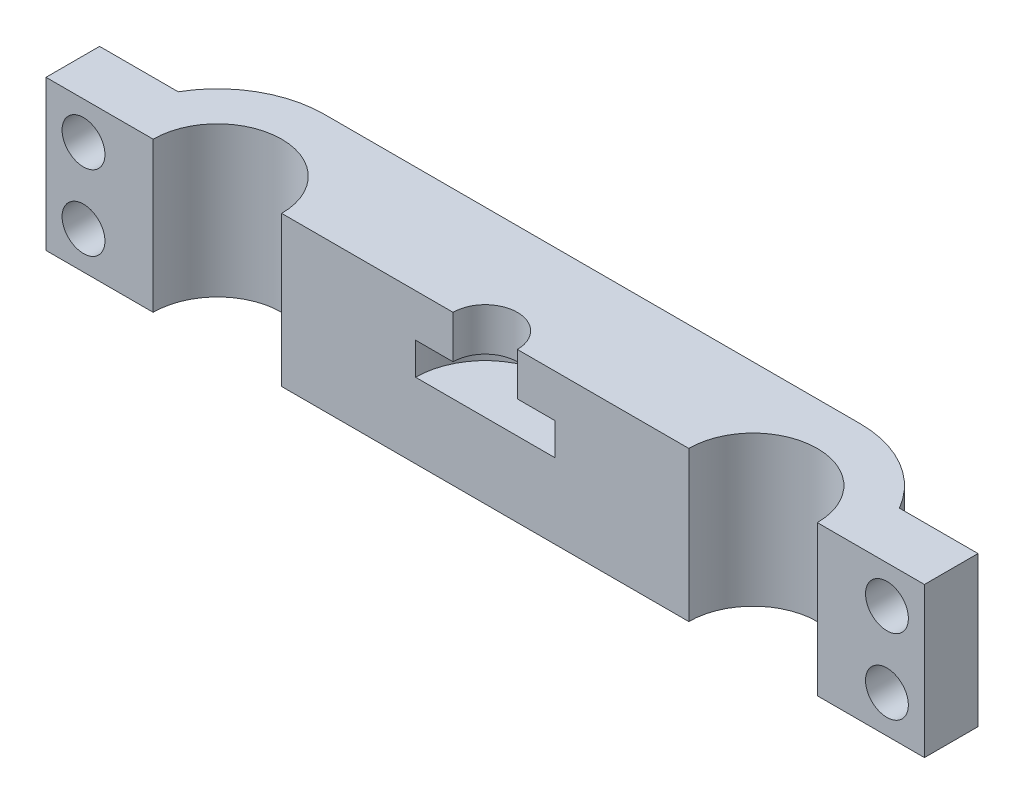
SolidWorks part; units mm, degrees
ref_plane "Front Plane" through (0, 0, 0) normal (0, 0, 1) x (1, 0, 0)
ref_plane "Top Plane" through (0, 0, 0) normal (0, 1, 0) x (1, 0, 0)
ref_plane "Right Plane" through (0, 0, 0) normal (1, 0, 0) x (0, 0, -1)
sketch "Sketch2" plane through (0, 0, 0) normal (0, 1, 0) x (1, 0, 0)
  line L0 (-3, 0) -> (-19, 0)
  line L1 (3, 0) -> (19, 0)
  line L2 (-31, 0) -> (-41, 0)
  line L3 (31, 0) -> (41, 0)
  line L4 (-41, 0) -> (-41, 5)
  line L5 (41, 0) -> (41, 5)
  line L6 (-25, 10) -> (25, 10)
  line L7 (-41, 5) -> (-33.6603, 5)
  line L8 (41, 5) -> (33.6603, 5)
  arc A1 (-19, 0) -> (-31, 0) centre (-25, 0) ccw
  arc A2 (31, 0) -> (19, 0) centre (25, 0) ccw
  arc A3 (3, 0) -> (-3, 0) centre (0, 0) ccw
  arc A4 (-25, 10) -> (-33.6603, 5) centre (-25, 0) ccw
  arc A5 (33.6603, 5) -> (25, 10) centre (25, 0) ccw
  dimension "D2" = 12
  dimension "D3" = 12
  dimension "D4" = 6
  dimension "D12" = 20
  dimension "D5" = 16
  dimension "D6" = 16
  dimension "D7" = 10
  dimension "D8" = 10
  dimension "D9" = 5
  dimension "D10" = 5
  dimension "D11" = 10
extrude "Boss-Extrude1" add sketch "Sketch2" along normal blind 14
sketch "Sketch4" plane through (0, 0, 0) normal (0, 0, 1) x (1, 0, 0)
  line L1 (-41, 0) -> (-31, 0) construction
  line L3 (-41, 14) -> (-41, 0) construction
  line L4 (41, 14) -> (41, 0) construction
  circle A0 centre (-37.5, 10.5) radius 2
  circle A1 centre (-37.5, 3.5) radius 2
  circle A2 centre (37.5, 10.5) radius 2
  circle A3 centre (37.5, 3.5) radius 2
  point P12 (0, 0)
  point P13 (0, 0)
  dimension "D1" = 4
  dimension "D2" = 4
  dimension "D4" = 3.5
  dimension "D6" = 4
  dimension "D7" = 4
  dimension "D3" = 7
  dimension "D5" = 3.5
  dimension "D8" = 7
  dimension "D9" = 3.5
extrude "Cut-Extrude1" cut sketch "Sketch4" against normal through all both and the other way through all
sketch "Sketch5" plane through (0, 0, 0) normal (0, -1, 0) x (1, 0, 0)
  line L0 (-4.6833, 0) -> (4.6254, 0)
  line L1 (-19, 0) -> (-3, 0) construction
  line L2 (3, 0) -> (19, 0) construction
  line L3 (4.6254, 0) -> (4.6254, -4.0444)
  line L4 (4.6254, -4.0444) -> (-4.6833, -4.0444)
  line L5 (-4.6833, -4.0444) -> (-4.6833, 0)
  point P7 (0, 0)
  point P9 (0, 0)
  point P10 (0, 0)
  point P11 (0, 0)
  dimension "D1" = 9.3087
  dimension "D2" = 4.0444
  dimension "D3" = 14.3167
extrude "Boss-Extrude2" add sketch "Sketch5" against normal blind 7
sketch "Sketch6" plane through (0, 7, 0) normal (0, 1, 0) x (1, 0, 0)
  circle A0 centre (0, 0) radius 6.5
  dimension "D1" = 13
extrude "Cut-Extrude2" cut sketch "Sketch6" against normal mid plane 3 from offset 1.5
